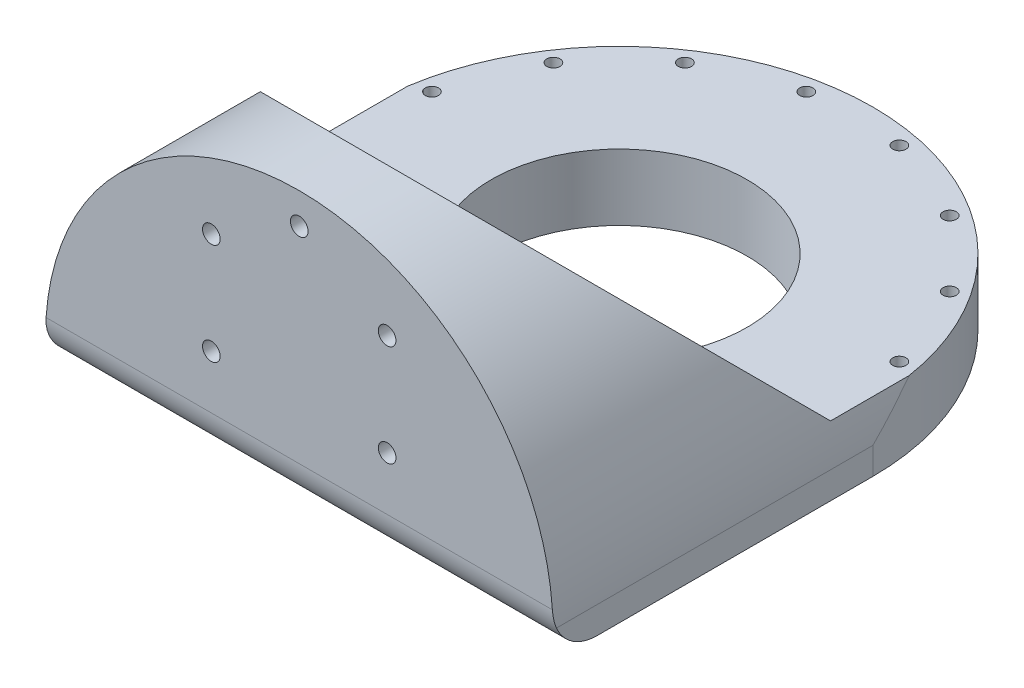
SolidWorks part; units mm, degrees
ref_plane "Front Plane" through (0, 0, 0) normal (0, 0, 1) x (1, 0, 0)
ref_plane "Top Plane" through (0, 0, 0) normal (0, 1, 0) x (1, 0, 0)
ref_plane "Right Plane" through (0, 0, 0) normal (1, 0, 0) x (0, 0, -1)
sketch "Sketch1" plane through (0, 0, 0) normal (0, 1, 0) x (1, 0, 0)
  line L0 (-10.5349, 52.9624) -> (0, 0) construction
  line L1 (0, 0) -> (0, 42.8379) construction
  line L2 (-57.5, 0) -> (-57.5, -57.5)
  line L3 (-57.5, -57.5) -> (57.5, -57.5)
  line L4 (57.5, -57.5) -> (57.5, 0)
  circle A0 centre (0, 0) radius 57.5
  circle A1 centre (0, 0) radius 29
  circle A2 centre (0, 0) radius 54 construction
  circle A3 centre (-10.5349, 52.9624) radius 1.5
  circle A4 centre (10.5349, 52.9624) radius 1.5
  circle A5 centre (30.0008, 44.8994) radius 1.5
  circle A6 centre (44.8994, 30.0008) radius 1.5
  circle A7 centre (52.9624, 10.5349) radius 1.5
  circle A8 centre (52.9624, -10.5349) radius 1.5
  circle A9 centre (44.8994, -30.0008) radius 1.5
  circle A10 centre (30.0008, -44.8994) radius 1.5
  circle A11 centre (10.5349, -52.9624) radius 1.5
  circle A12 centre (-10.5349, -52.9624) radius 1.5
  circle A13 centre (-30.0008, -44.8994) radius 1.5
  circle A14 centre (-44.8994, -30.0008) radius 1.5
  circle A15 centre (-52.9624, -10.5349) radius 1.5
  circle A16 centre (-52.9624, 10.5349) radius 1.5
  circle A17 centre (-44.8994, 30.0008) radius 1.5
  circle A18 centre (-30.0008, 44.8994) radius 1.5
  point P40 (0, 0)
  dimension "D1" = 115
  dimension "D2" = 58
  dimension "D3" = 108
  dimension "D4" = 3
  dimension "D5" = 11.25
  dimension "D6" = 16
extrude "Boss-Extrude1" add sketch "Sketch1" along normal blind 15 contours A0 A18 A17 A16 A15 A14 A13 A12 A11 A10 A9 A8 A7 A6 A5 A4 A3 A1 | A0 L2 L3 | A0 L3 L4
sketch "Sketch2" plane through (-57.5, 0, 0) normal (-1, 0, 0) x (0, 0, 1)
  line L0 (57.5, 0) -> (57.5, 63.6)
  line L1 (57.5, 63.6) -> (72.5, 63.6)
  line L2 (72.5, 63.6) -> (72.5, 0)
  line L3 (72.5, 0) -> (57.5, 0)
  line L4 (57.5, 63.6) -> (0, 15)
  line L5 (0, 15) -> (57.5, 15)
  line M6 (57.5, 0) -> (57.5, 15)
  line M7 (57.5, 15) -> (0, 15)
  dimension "D1" = 15
  dimension "D2" = 63.6
extrude "Boss-Extrude2" add sketch "Sketch2" against normal blind 115 contours L3 L2 L1 L0 M6 | L0 L4 M7
sketch "Sketch3" plane through (0, 63.6, 0) normal (0, 1, 0) x (1, 0, 0)
  circle A0 centre (0, 0) radius 57.5
extrude "Cut-Extrude1" cut sketch "Sketch3" against normal up to surface (48.6 mm away) up to face at (0, 15, -21.625)
sketch "Sketch5" plane through (0, 0, 72.5) normal (0, 0, 1) x (1, 0, 0)
  line L0 (0, 76.0834) -> (0, 0) construction
  line L1 (57.5, 63.6) -> (-57.5, 63.6) construction
  circle A0 centre (0, 33.6) radius 23 construction
  circle A1 centre (0, 33.6) radius 30 construction
  circle A2 centre (0, 56.6) radius 2
  circle A3 centre (-19.9186, 45.1) radius 2
  circle A4 centre (-19.9186, 22.1) radius 2
  circle A6 centre (19.9186, 22.1) radius 2
  circle A7 centre (19.9186, 45.1) radius 2
  circle A8 centre (0, 10.6) radius 2 [skipped]
  point P22 (0, 33.6)
  dimension "D1" = 46
  dimension "D2" = 60
  dimension "D3" = 4
  dimension "D4" = 6
extrude "Cut-Extrude3" cut sketch "Sketch5" against normal blind 75.6
sketch "Sketch6" plane through (0, 0, 0) normal (0, 0, 1) x (1, 0, 0)
  line L0 (57.5, 63.6) -> (-57.5, 63.6) construction
  circle A0 centre (0, 33.6) radius 23 construction
  circle A1 centre (0, 33.6) radius 30 construction
  circle A2 centre (0, 56.6) radius 4.25
  circle A3 centre (19.9186, 45.1) radius 4.25
  circle A4 centre (19.9186, 22.1) radius 4.25
  circle A6 centre (-19.9186, 22.1) radius 4.25
  circle A7 centre (-19.9186, 45.1) radius 4.25
  circle A8 centre (0, 10.6) radius 4.25 [skipped]
  point P19 (0, 33.6)
  dimension "D1" = 46
  dimension "D2" = 60
  dimension "D3" = 8.5
  dimension "D4" = 6
extrude "Cut-Extrude4" cut sketch "Sketch6" along normal blind 62.5
sketch "Sketch4" plane through (0, 0, 72.5) normal (0, 0, 1) x (1, 0, 0)
  line L0 (0, 71.5981) -> (0, -19.7592) construction
  line L1 (57.5, 63.6) -> (-57.5, 63.6) construction
  line L2 (-57.5, 0) -> (-57.5, 63.6)
  line L3 (-57.5, 63.6) -> (0, 63.6)
  line L4 (0, 63.6) -> (57.5, 63.6)
  line L5 (57.5, 63.6) -> (57.5, 0)
  circle A0 centre (0, 6.1) radius 57.5
  line M2 (-57.5, 63.6) -> (-57.5, 0)
  line M5 (57.5, 63.6) -> (-57.5, 63.6)
  dimension "D1" = 115
extrude "Cut-Extrude2" cut sketch "Sketch4" against normal blind 132.6 contours A0 M5 M2 | A0 L5 M5
fillet "Fillet1" radius 10 1 edges at (0, 0, 72.5)
